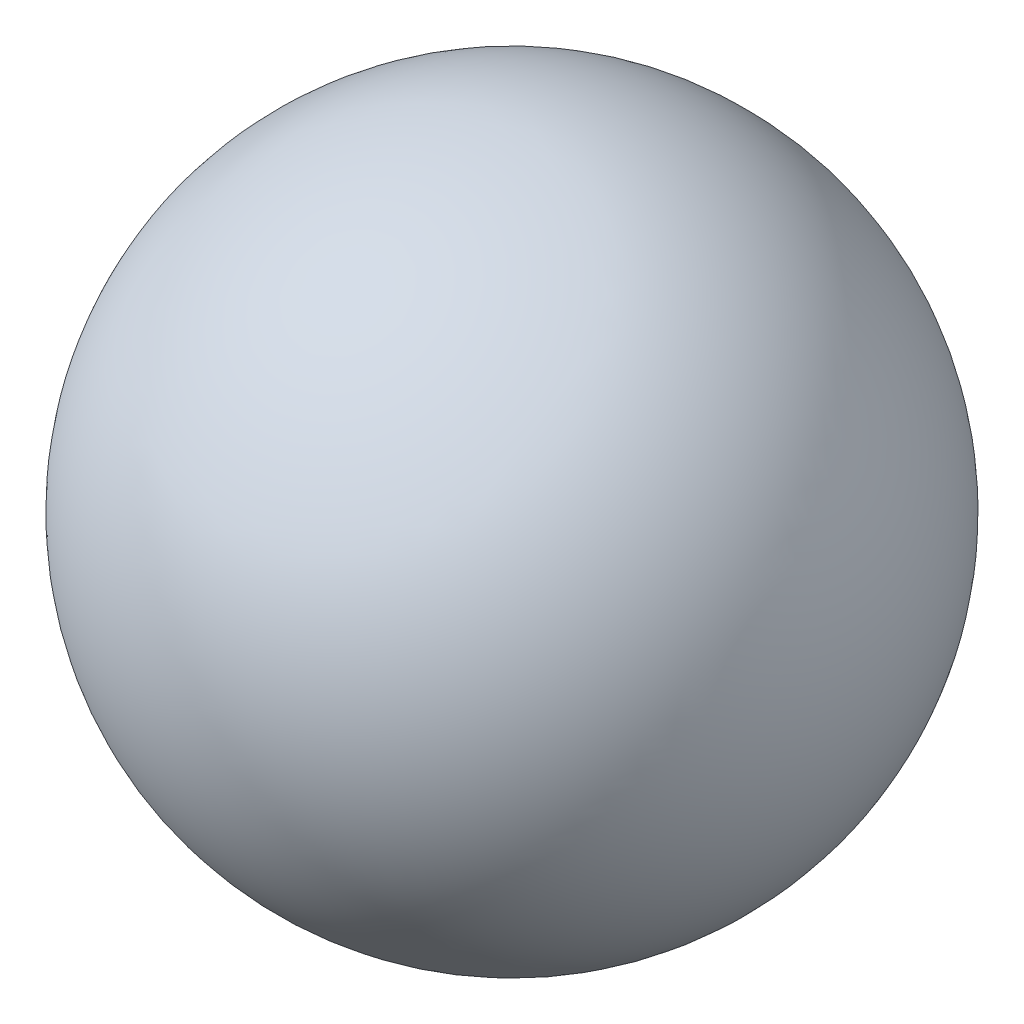
SolidWorks part; units mm, degrees
ref_plane "Front Plane" through (0, 0, 0) normal (0, 0, 1) x (1, 0, 0)
ref_plane "Top Plane" through (0, 0, 0) normal (0, 1, 0) x (1, 0, 0)
ref_plane "Right Plane" through (0, 0, 0) normal (1, 0, 0) x (0, 0, -1)
ref_plane "Plane1" through (0, 0, 0) normal (0, 0, -1) x (-1, 0, 0)
sketch "Sketch1" plane through (0, 0, 0) normal (0, 0, -1) x (-1, 0, 0)
  line L0 (3.21, 0) -> (4.7275, 0)
  line L1 (3.21, 0) -> (4.7275, 0) construction
  arc A0 (4.7275, 0) -> (3.21, 0) centre (3.9688, 0) ccw
revolve "Revolve1" add sketch "Sketch1" angle 360 about L1
